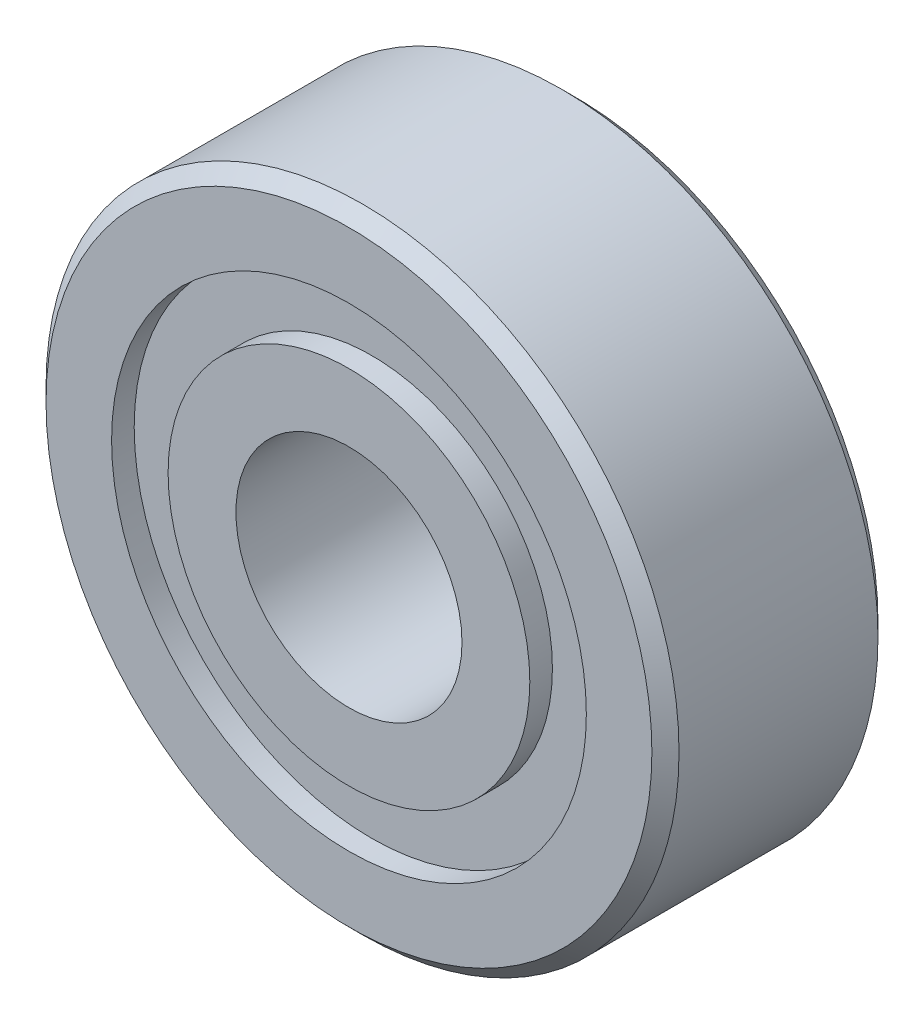
SolidWorks part; units mm, degrees
ref_plane "Front Plane" through (0, 0, 0) normal (0, 0, 1) x (1, 0, 0)
ref_plane "Top Plane" through (0, 0, 0) normal (0, 1, 0) x (1, 0, 0)
ref_plane "Right Plane" through (0, 0, 0) normal (1, 0, 0) x (0, 0, -1)
sketch "Sketch1" plane through (0, 0, 0) normal (0, 0, 1) x (1, 0, 0)
  circle A0 centre (0, 0) radius 2.5
  circle A1 centre (0, 0) radius 7
  dimension "D1" = 14
  dimension "D2" = 5
extrude "Boss-Extrude1" add sketch "Sketch1" along normal blind 5
sketch "Sketch2" plane through (0, 0, 5) normal (0, 0, 1) x (1, 0, 0)
  circle A0 centre (0, 0) radius 4
  circle A1 centre (0, 0) radius 5.25
  dimension "D1" = 8
  dimension "D2" = 10.5
extrude "Cut-Extrude1" cut sketch "Sketch2" against normal blind 0.5
sketch "Sketch3" plane through (0, 0, 0) normal (0, 0, -1) x (-1, 0, 0)
  circle A1 centre (0, 0) radius 5.25
  circle A2 centre (0, 0) radius 5.25
  circle A3 centre (0, 0) radius 4
  circle A4 centre (0, 0) radius 4
  dimension "D1" = 0
  dimension "D2" = 0
extrude "Cut-Extrude2" cut sketch "Sketch3" against normal blind 0.5
chamfer "Chamfer1" distance 0.3 angle 45 2 edges at (7, 0, 5) (7, 0, 0)
